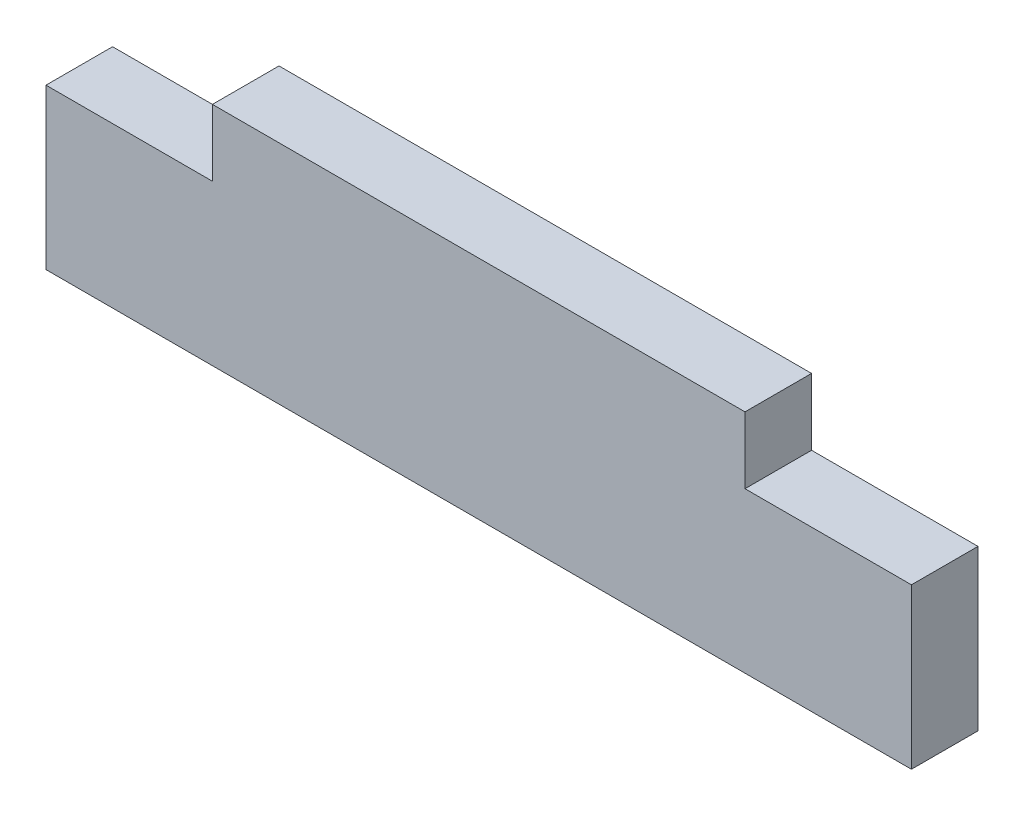
SolidWorks part; units mm, degrees
ref_plane "Front" through (0, 0, 0) normal (0, 0, 1) x (1, 0, 0)
ref_plane "Top" through (0, 0, 0) normal (0, 1, 0) x (1, 0, 0)
ref_plane "Right" through (0, 0, 0) normal (1, 0, 0) x (0, 0, -1)
sketch "Skizze1" plane through (0, 0, 0) normal (0, 0, 1) x (1, 0, 0)
  line L0 (0, 0) -> (0, 17) construction
  line L1 (20, 17) -> (-20, 17)
  line L2 (-20, 17) -> (-20, 12)
  line L3 (-20, 12) -> (-32.5, 12)
  line L4 (-32.5, 12) -> (-32.5, 0)
  line L5 (-32.5, 0) -> (32.5, 0)
  line L6 (32.5, 12) -> (32.5, 0)
  line L7 (20, 12) -> (32.5, 12)
  line L8 (20, 17) -> (20, 12)
  dimension "D1" = 5
  dimension "D2" = 12
  dimension "D3" = 40
  dimension "D4" = 65
extrude "Aufsatz-Linear austragen1" add sketch "Skizze1" along normal blind 5
